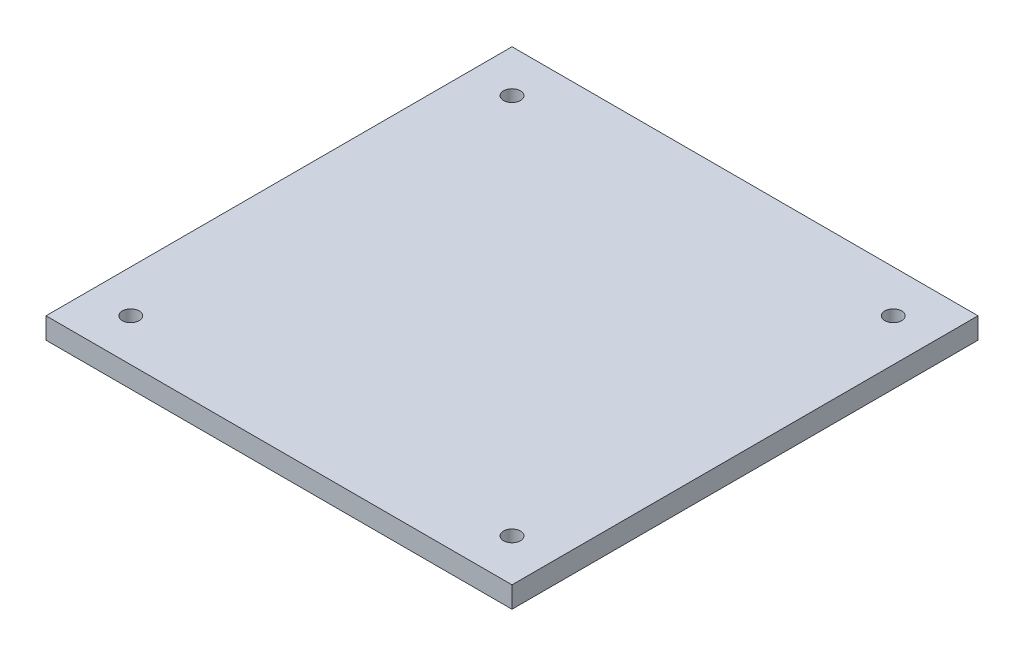
SolidWorks part; units mm, degrees
ref_plane "Plano frontal" through (0, 0, 0) normal (0, 0, 1) x (1, 0, 0)
ref_plane "Plano superior" through (0, 0, 0) normal (0, 1, 0) x (1, 0, 0)
ref_plane "Plano direito" through (0, 0, 0) normal (1, 0, 0) x (0, 0, -1)
sketch "Esboço1" plane through (0, 0, 0) normal (0, 1, 0) x (1, 0, 0)
  line L1 (-98.2759, -57.7155) -> (121.7241, -57.7155)
  line L2 (-98.2759, -57.7155) -> (-98.2759, 162.2845)
  line L3 (-98.2759, 162.2845) -> (121.7241, 162.2845)
  line L4 (121.7241, -57.7155) -> (121.7241, 162.2845)
  dimension "D1" = 220
  dimension "D2" = 220
extrude "Ressalto-extrusão1" add sketch "Esboço1" along normal blind 10
sketch "Esboço2" plane through (0, 10, 0) normal (0, 1, 0) x (1, 0, 0)
  line L0 (121.7241, 162.2845) -> (-98.2759, 162.2845) construction
  line L1 (-98.2759, 162.2845) -> (-98.2759, -57.7155) construction
  line L2 (-98.2759, 52.2845) -> (121.7241, 52.2845) construction
  line L3 (121.7241, -57.7155) -> (121.7241, 162.2845) construction
  line L4 (11.7241, 162.2845) -> (11.7241, -57.7155) construction
  line L5 (-98.2759, -57.7155) -> (121.7241, -57.7155) construction
  circle A0 centre (-78.2759, 142.2845) radius 4
  circle A1 centre (101.7241, 142.2845) radius 4
  circle A2 centre (101.7241, -37.7155) radius 4
  circle A3 centre (-78.2759, -37.7155) radius 4
  dimension "D1" = 8
  dimension "D2" = 20
  dimension "D3" = 20
extrude "Corte-extrusão1" cut sketch "Esboço2" against normal through all
